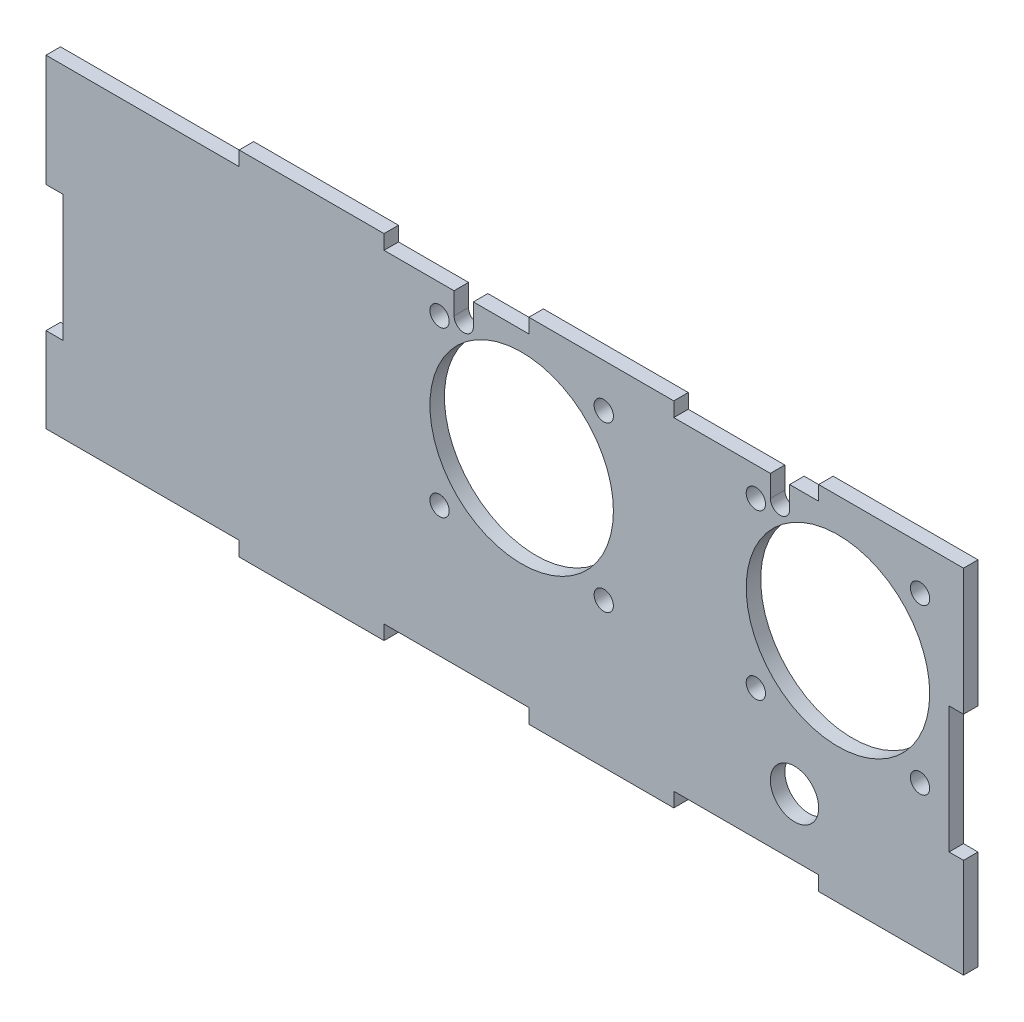
SolidWorks part; units mm, degrees
material "Acrylic (Medium-high impact)"
ref_plane "Front Plane" through (0, 0, 0) normal (0, 0, 1) x (1, 0, 0)
ref_plane "Top Plane" through (0, 0, 0) normal (0, 1, 0) x (1, 0, 0)
ref_plane "Right Plane" through (0, 0, 0) normal (1, 0, 0) x (0, 0, -1)
sketch "Sketch1" plane through (0, 0, 0) normal (0, 0, 1) x (1, 0, 0)
  line L252 (0, 70) -> (0, 73)
  line L253 (0, 70) -> (-10, 70)
  line L254 (60, 73) -> (90, 73)
  line L255 (0, 0) -> (180, 0)
  line L256 (0, 0) -> (0, 3)
  line L257 (0, 73) -> (180, 73)
  line L258 (180, 0) -> (180, 73)
  line L259 (0, 73) -> (30, 73)
  line L260 (0, 73) -> (0, 70)
  line L261 (0, 70) -> (30, 70)
  line L262 (30, 73) -> (30, 70)
  line L263 (60, 73) -> (60, 70)
  line L264 (60, 70) -> (90, 70)
  line L265 (90, 73) -> (90, 70)
  line L266 (120, 73) -> (150, 73)
  line L267 (120, 73) -> (120, 70)
  line L268 (120, 70) -> (150, 70)
  line L269 (150, 73) -> (150, 70)
  line L270 (60, 3) -> (90, 3)
  line L271 (60, 3) -> (60, 0)
  line L272 (60, 0) -> (90, 0)
  line L273 (90, 3) -> (90, 0)
  line L274 (120, 3) -> (150, 3)
  line L275 (120, 3) -> (120, 0)
  line L276 (120, 0) -> (150, 0)
  line L277 (150, 3) -> (150, 0)
  line L278 (0, 3) -> (30, 3)
  line L279 (0, 3) -> (0, 0)
  line L280 (0, 0) -> (30, 0)
  line L281 (30, 3) -> (30, 0)
  line L282 (177, 46.8) -> (177, 20.6)
  line L287 (177, 46.8) -> (180, 46.8)
  line L288 (180, 46.8) -> (180, 20.6)
  line L289 (177, 20.6) -> (180, 20.6)
  line L290 (-10, 70) -> (-10, 3)
  line L291 (-10, 3) -> (0, 3)
  line L293 (-10, 46.8) -> (-6.4736, 46.8)
  line L294 (-10, 46.8) -> (-10, 20.6)
  line L295 (-10, 20.6) -> (-6.4736, 20.6)
  line L296 (-6.4736, 46.8) -> (-6.4736, 20.6)
  circle A0 centre (145, 15) radius 5
  dimension "D7" = 10
  dimension "D1" = 180
  dimension "D2" = 73
  dimension "D3" = 3
  dimension "D4" = 30
  dimension "D8" = 3
  dimension "D5" = 23.2
  dimension "D6" = 26.2
  dimension "D12" = 10
  dimension "D10" = 35
  dimension "D11" = 12
  dimension "D9" = 2
extrude "Boss-Extrude1" add sketch "Sketch1" along normal blind 3
sketch "Sketch2" plane through (0, 0, 3) normal (0, 0, 1) x (1, 0, 0)
  line L0 (154, 67) -> (154, 27) construction
  line L1 (137, 27) -> (171, 27)
  line L2 (134, 30) -> (134, 64)
  line L3 (137, 67) -> (171, 67)
  line L4 (174, 30) -> (174, 64)
  line L5 (134, 47) -> (174, 47) construction
  line L6 (88.5, 67) -> (88.5, 27) construction
  line L7 (71.5, 27) -> (105.5, 27)
  line L8 (68.5, 30) -> (68.5, 64)
  line L9 (71.5, 67) -> (105.5, 67)
  line L10 (108.5, 30) -> (108.5, 64)
  line L11 (68.5, 47) -> (108.5, 47) construction
  line L12 (180, 46.8) -> (180, 73) construction
  line L13 (150, 0) -> (180, 0) construction
  line L14 (90, 0) -> (120, 0) construction
  line L15 (60, 70) -> (90, 70) construction
  line L17 (74.5, 65.5) -> (74.5, 70)
  line L18 (74.5, 70) -> (78.5, 70)
  line L19 (78.5, 65.5) -> (78.5, 70)
  line L20 (140, 65.5) -> (140, 70)
  line L21 (140, 70) -> (144, 70)
  line L22 (144, 65.5) -> (144, 70)
  line L23 (120, 70) -> (150, 70) construction
  arc A0 (171, 67) -> (174, 64) centre (171, 64) cw
  arc A1 (174, 30) -> (171, 27) centre (171, 30) cw
  arc A2 (134, 30) -> (137, 27) centre (137, 30) ccw
  arc A3 (134, 64) -> (137, 67) centre (137, 64) cw
  circle A4 centre (154, 47) radius 19
  circle A5 centre (137, 64) radius 2
  circle A6 centre (171, 64) radius 2
  circle A7 centre (171, 30) radius 2
  circle A8 centre (137, 30) radius 2
  arc A9 (105.5, 67) -> (108.5, 64) centre (105.5, 64) cw
  arc A10 (108.5, 30) -> (105.5, 27) centre (105.5, 30) cw
  arc A11 (68.5, 30) -> (71.5, 27) centre (71.5, 30) ccw
  arc A12 (68.5, 64) -> (71.5, 67) centre (71.5, 64) cw
  circle A13 centre (88.5, 47) radius 19
  circle A14 centre (71.5, 64) radius 2
  circle A15 centre (105.5, 64) radius 2
  circle A16 centre (105.5, 30) radius 2
  circle A17 centre (71.5, 30) radius 2
  arc A18 (74.5, 65.5) -> (78.5, 65.5) centre (76.5, 65.5) ccw
  arc A19 (140, 65.5) -> (144, 65.5) centre (142, 65.5) ccw
  point P51 (76.5519, 65.4829)
  point P63 (141.8472, 65.0051)
  line M30 (150, 70) -> (120, 70)
  dimension "D1" = 3
  dimension "D6" = 38
  dimension "D7" = 4
  dimension "D9" = 3
  dimension "D14" = 38
  dimension "D15" = 4
  dimension "D21" = 4
  dimension "D22" = 4.5
  dimension "D24" = 4
  dimension "D25" = 5
  dimension "D2" = 34
  dimension "D3" = 34
  dimension "D4" = 20
  dimension "D5" = 20
  dimension "D8" = 3
  dimension "D10" = 34
  dimension "D11" = 34
  dimension "D12" = 20
  dimension "D13" = 20
  dimension "D16" = 3
  dimension "D17" = 71.5
  dimension "D18" = 6
  dimension "D19" = 27
  dimension "D20" = 27
  dimension "D23" = 5
  dimension "D26" = 4.5
extrude "Cut-Extrude1" cut sketch "Sketch2" against normal blind 10 contours A15 | A4 | A13 | L3 L22 L20 M30 | L20 A19 L22 L3 | A14 | A17 | A16 | A8 | A7 | A6 | A5 | L18 L19 A18 L17
